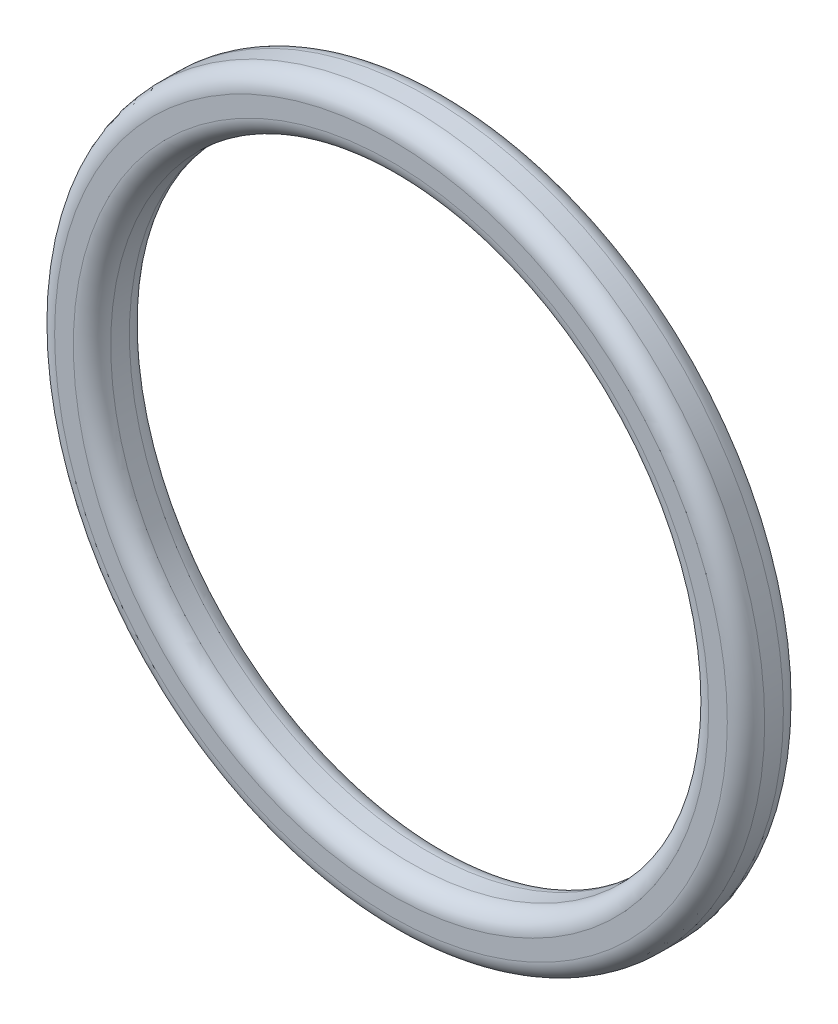
SolidWorks part; units mm, degrees
ref_plane "Front Plane" through (0, 0, 0) normal (0, 0, 1) x (1, 0, 0)
ref_plane "Top Plane" through (0, 0, 0) normal (0, 1, 0) x (1, 0, 0)
ref_plane "Right Plane" through (0, 0, 0) normal (1, 0, 0) x (0, 0, -1)
sketch "Sketch1" plane through (0, 0, 0) normal (0, 0, 1) x (1, 0, 0)
  circle A0 centre (0, 0) radius 8
  circle A1 centre (0, 0) radius 9.5
  dimension "D1" = 16
  dimension "D2" = 19
extrude "Boss-Extrude1" add sketch "Sketch1" along normal blind 1.5
fillet "Fillet1" radius 0.5 4 edges at (8, 0, 0) (9.5, 0, 0) (8, 0, 1.5) (9.5, 0, 1.5)
